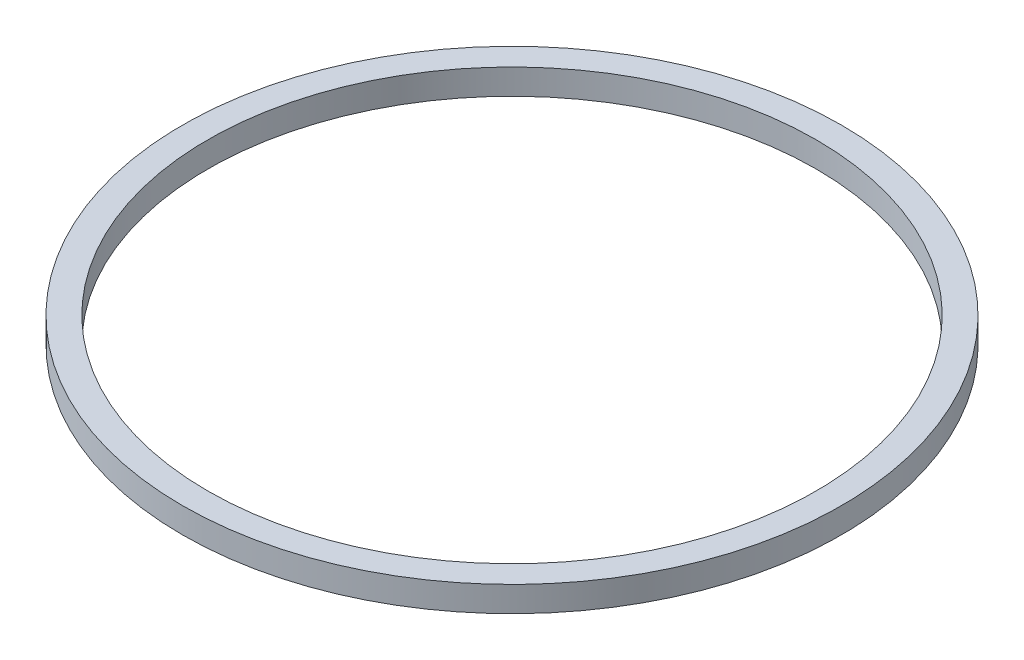
SolidWorks part; units mm, degrees
ref_plane "Front Plane" through (0, 0, 0) normal (0, 0, 1) x (1, 0, 0)
ref_plane "Top Plane" through (0, 0, 0) normal (0, 1, 0) x (1, 0, 0)
ref_plane "Right Plane" through (0, 0, 0) normal (1, 0, 0) x (0, 0, -1)
sketch "Sketch1" plane through (0, 0, 0) normal (0, 1, 0) x (1, 0, 0)
  circle A0 centre (0, 0) radius 13
  circle A1 centre (0, 0) radius 12
  dimension "D1" = 1
  dimension "D2" = 24
extrude "Boss-Extrude1" add sketch "Sketch1" along normal blind 1
